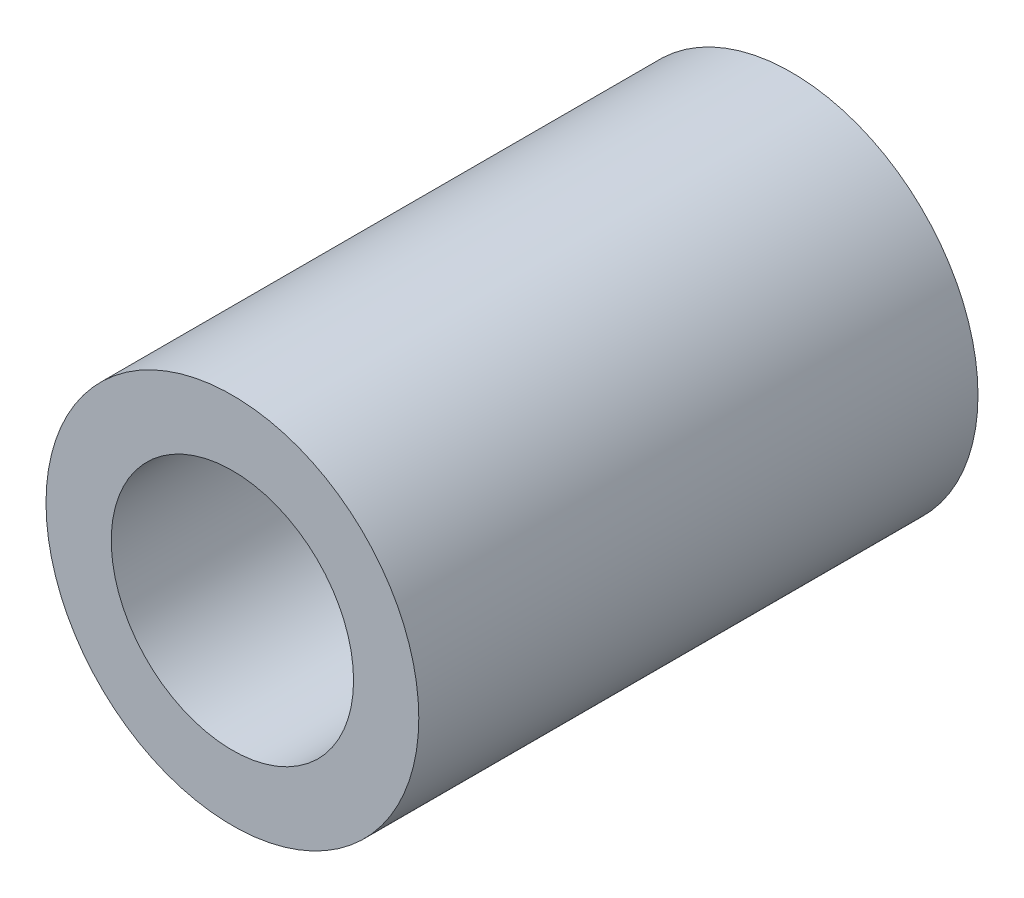
SolidWorks part; units mm, degrees
ref_plane "Alzado" through (0, 0, 0) normal (0, 0, 1) x (1, 0, 0)
ref_plane "Planta" through (0, 0, 0) normal (0, 1, 0) x (1, 0, 0)
ref_plane "Vista lateral" through (0, 0, 0) normal (1, 0, 0) x (0, 0, -1)
sketch "Croquis1" plane through (0, 0, 0) normal (0, 0, 1) x (1, 0, 0)
  circle A0 centre (0, 0) radius 4
  circle A1 centre (0, 0) radius 2.6
  dimension "D1" = 8
  dimension "D2" = 5.2
extrude "Saliente-Extruir1" add sketch "Croquis1" along normal blind 12
